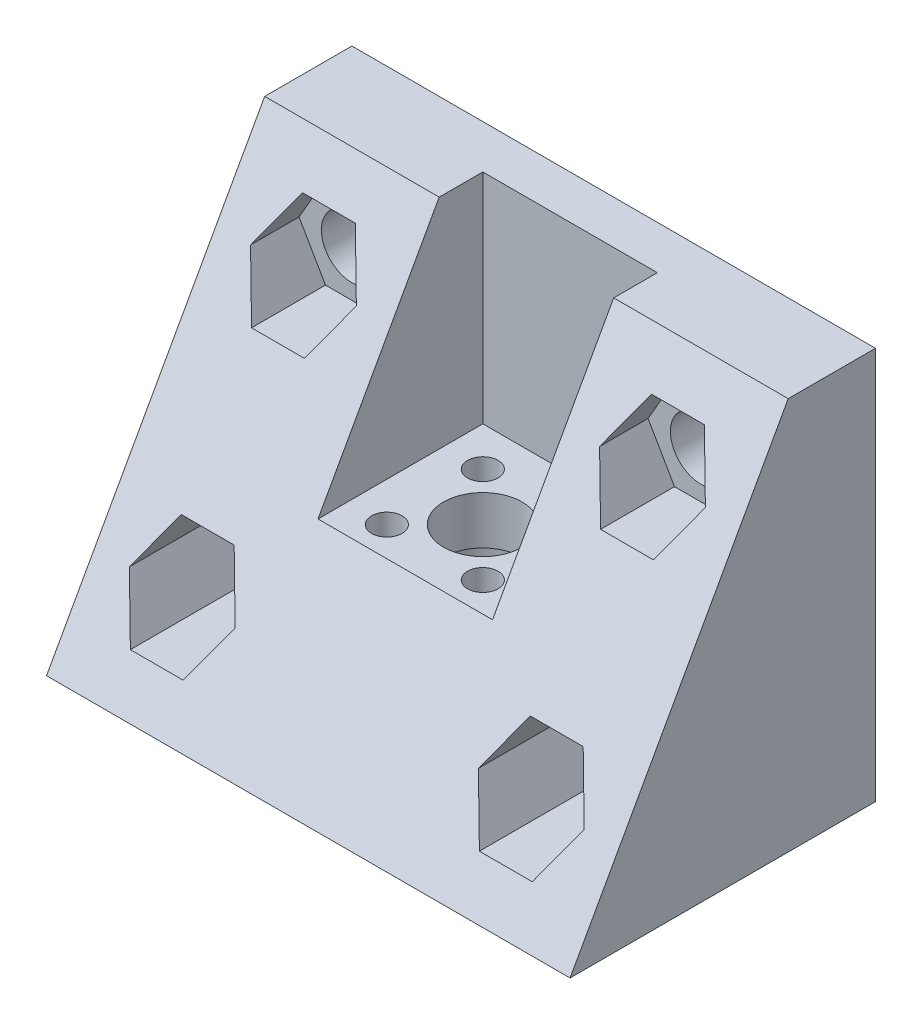
SolidWorks part; units mm, degrees
ref_plane "Front Plane" through (0, 0, 0) normal (0, 0, 1) x (1, 0, 0)
ref_plane "Top Plane" through (0, 0, 0) normal (0, 1, 0) x (1, 0, 0)
ref_plane "Right Plane" through (0, 0, 0) normal (1, 0, 0) x (0, 0, -1)
sketch "Sketch1" plane through (0, 0, 0) normal (0, 0, 1) x (1, 0, 0)
  line L1 (0, 0) -> (60, 0)
  line L2 (0, 0) -> (0, 45)
  line L3 (0, 45) -> (60, 45)
  line L4 (60, 0) -> (60, 45)
  dimension "D1" = 60
  dimension "D2" = 45
extrude "Boss-Extrude1" add sketch "Sketch1" along normal blind 35
sketch "Sketch2" plane through (0, 0, 0) normal (0, -1, 0) x (1, 0, 0)
  line L0 (0, 35) -> (0, 0) construction
  line L1 (0, 0) -> (60, 0) construction
  circle A0 centre (30, 15) radius 4.5
  dimension "D1" = 30
  dimension "D2" = 9
  dimension "D3" = 15
extrude "Cut-Extrude1" cut sketch "Sketch2" against normal blind 50
sketch "Sketch3" plane through (0, 0, 0) normal (0, -1, 0) x (1, 0, 0)
  circle A0 centre (30, 15) radius 11.25
  dimension "D1" = 22.5
extrude "Cut-Extrude2" cut sketch "Sketch3" against normal blind 4
sketch "Sketch6" plane through (0, 0, 35) normal (0, 0, 1) x (1, 0, 0)
  line L0 (60, 45) -> (0, 45) construction
  line L1 (40, 45) -> (20, 45)
  line L2 (40, 45) -> (40, 20)
  line L3 (40, 20) -> (20, 20)
  line L4 (20, 45) -> (20, 20)
  line L5 (60, 0) -> (60, 45) construction
  line L6 (0, 45) -> (0, 0) construction
  dimension "D1" = 20
  dimension "D2" = 20
  dimension "D3" = 25
extrude "Cut-Extrude4" cut sketch "Sketch6" against normal blind 30
sketch "Sketch4" plane through (60, 0, 0) normal (1, 0, 0) x (0, 0, -1)
  line L0 (-35, 0) -> (-10, 45)
  line L1 (-35, 45) -> (0, 45) construction
  line L2 (-10, 45) -> (-35, 45)
  line L3 (-35, 0) -> (-35, 45) construction
  line L4 (-35, 45) -> (-35, 0)
  dimension "D1" = 25
extrude "Cut-Extrude3" cut sketch "Sketch4" against normal blind 80
sketch "Sketch7" plane through (0, 4, 0) normal (0, -1, 0) x (1, 0, 0)
  circle A0 centre (24.5, 20.5) radius 1.75
  circle A1 centre (35.5, 20.5) radius 1.75
  circle A2 centre (35.5, 9.5) radius 1.75
  circle A3 centre (24.5, 9.5) radius 1.75
  circle A4 centre (30, 15) radius 4.5 construction
  dimension "D1" = 3.5
  dimension "D2" = 3.5
  dimension "D3" = 3.5
  dimension "D4" = 3.5
  dimension "D5" = 11
  dimension "D6" = 5.5
  dimension "D7" = 5.5
  dimension "D8" = 5.5
  dimension "D9" = 11
  dimension "D10" = 11
  dimension "D11" = 5.5
  dimension "D12" = 5.5
extrude "Cut-Extrude5" cut sketch "Sketch7" against normal blind 25
sketch "Sketch8" plane through (0, 0, 0) normal (0, 0, -1) x (-1, 0, 0)
  line L0 (0, 0) -> (-60, 0) construction
  line L1 (-60, 0) -> (-60, 45) construction
  line L2 (-60, 45) -> (0, 45) construction
  line L3 (0, 45) -> (0, 0) construction
  circle A0 centre (-50, 10) radius 3.5
  circle A1 centre (-50, 35) radius 3.5
  circle A2 centre (-10, 35) radius 3.5
  circle A3 centre (-10, 10) radius 3.5
  dimension "D1" = 10
  dimension "D2" = 10
  dimension "D3" = 10
  dimension "D4" = 10
  dimension "D5" = 7
  dimension "D6" = 7
  dimension "D7" = 7
  dimension "D8" = 7
  dimension "D9" = 10
  dimension "D10" = 10
  dimension "D11" = 10
  dimension "D12" = 10
extrude "Cut-Extrude6" cut sketch "Sketch8" against normal blind 44
sketch "Sketch9" plane through (0, 0, 0) normal (0, 0, 1) x (1, 0, 0)
  line L0 (0, 0) -> (60, 0) construction
  line L1 (6.9689, 40.25) -> (3.9378, 35)
  line L2 (3.9378, 35) -> (6.9689, 29.75)
  line L3 (6.9689, 29.75) -> (13.0311, 29.75)
  line L4 (13.0311, 29.75) -> (16.0622, 35)
  line L5 (16.0622, 35) -> (13.0311, 40.25)
  line L6 (13.0311, 40.25) -> (6.9689, 40.25)
  line L7 (13.0311, 4.75) -> (16.0622, 10)
  line L8 (16.0622, 10) -> (13.0311, 15.25)
  line L9 (13.0311, 15.25) -> (6.9689, 15.25)
  line L10 (6.9689, 15.25) -> (3.9378, 10)
  line L11 (3.9378, 10) -> (6.9689, 4.75)
  line L12 (6.9689, 4.75) -> (13.0311, 4.75)
  line L13 (53.0311, 29.75) -> (56.0622, 35)
  line L14 (56.0622, 35) -> (53.0311, 40.25)
  line L15 (53.0311, 40.25) -> (46.9689, 40.25)
  line L16 (46.9689, 40.25) -> (43.9378, 35)
  line L17 (43.9378, 35) -> (46.9689, 29.75)
  line L18 (46.9689, 29.75) -> (53.0311, 29.75)
  line L19 (53.0311, 4.75) -> (56.0622, 10)
  line L20 (56.0622, 10) -> (53.0311, 15.25)
  line L21 (53.0311, 15.25) -> (46.9689, 15.25)
  line L22 (46.9689, 15.25) -> (43.9378, 10)
  line L23 (43.9378, 10) -> (46.9689, 4.75)
  line L24 (46.9689, 4.75) -> (53.0311, 4.75)
  line L25 (40, 45) -> (60, 45) construction
  line L26 (0, 45) -> (20, 45) construction
  circle A0 centre (10, 35) radius 5.25 construction
  circle A1 centre (10, 10) radius 5.25 construction
  circle A2 centre (50, 35) radius 5.25 construction
  circle A3 centre (50, 10) radius 5.25 construction
  point P28 (50, 40.25)
  dimension "D1" = 10.5
  dimension "D2" = 10.5
  dimension "D3" = 10.5
  dimension "D4" = 10.5
  dimension "D5" = 0
  dimension "D6" = 0
  dimension "D7" = 0
  dimension "D8" = 0
extrude "Cut-Extrude7" cut sketch "Sketch9" against normal blind 25 from offset 35
sketch "Sketch10" plane through (0, 4, 0) normal (0, -1, 0) x (1, 0, 0)
  circle A0 centre (30, 15) radius 5.1
  dimension "D1" = 10.2
extrude "Cut-Extrude8" cut sketch "Sketch10" against normal blind 10.5
